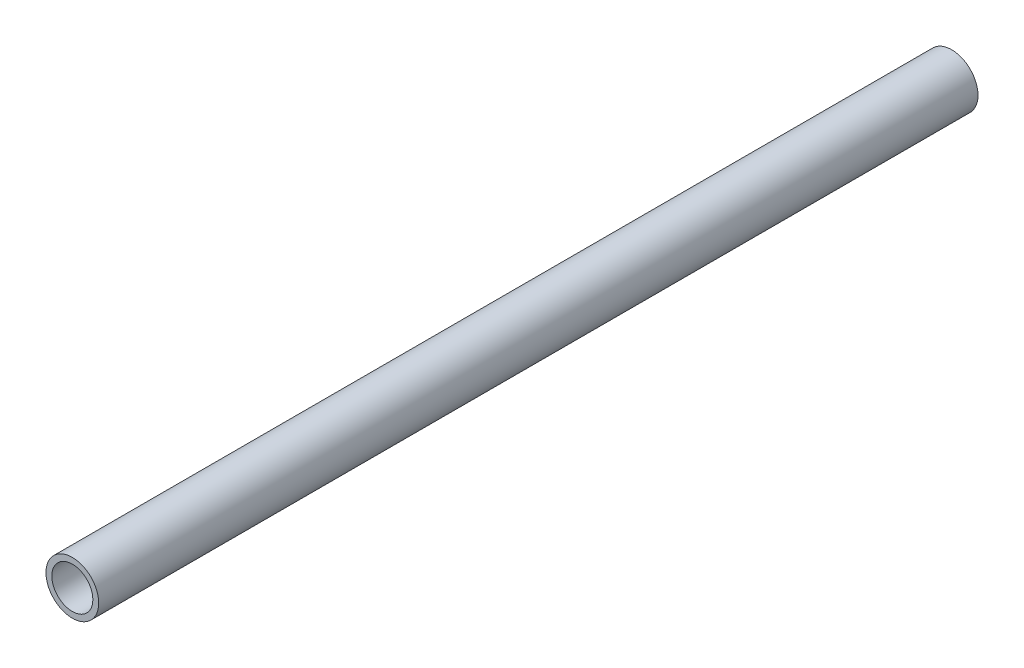
SolidWorks part; units mm, degrees
ref_plane "前视基准面" through (0, 0, 0) normal (0, 0, 1) x (1, 0, 0)
ref_plane "上视基准面" through (0, 0, 0) normal (0, 1, 0) x (1, 0, 0)
ref_plane "右视基准面" through (0, 0, 0) normal (1, 0, 0) x (0, 0, -1)
other "Configuration Table"
sketch "草图1" plane through (0, 0, 0) normal (0, 0, 1) x (1, 0, 0)
  circle A0 centre (0, 0) radius 7
  circle A1 centre (0, 0) radius 9
  dimension "D2" = 14
  dimension "D1" = 2
extrude "凸台-拉伸1" add sketch "草图1" along normal blind 300.06
